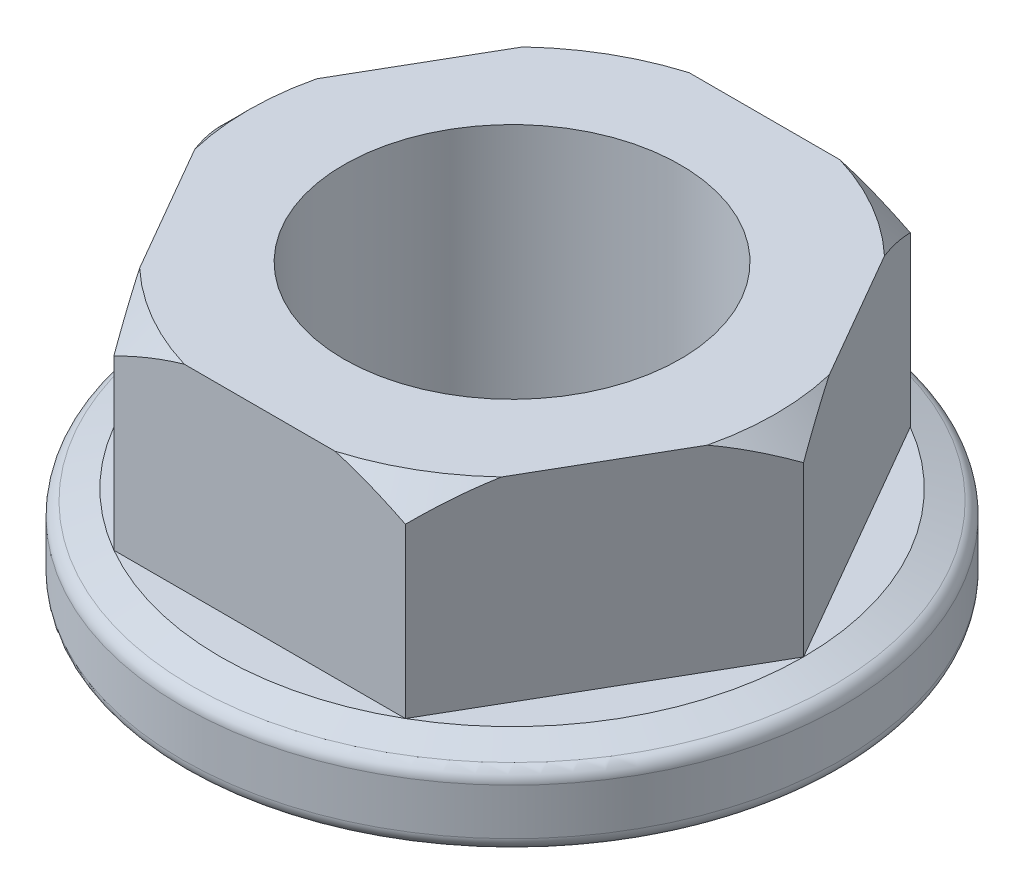
SolidWorks part; units mm, degrees
ref_plane "Front Plane" through (0, 0, 0) normal (0, 0, 1) x (1, 0, 0)
ref_plane "Top Plane" through (0, 0, 0) normal (0, 1, 0) x (1, 0, 0)
ref_plane "Right Plane" through (0, 0, 0) normal (1, 0, 0) x (0, 0, -1)
sketch "Sketch1" plane through (0, 0, 0) normal (0, 1, 0) x (1, 0, 0)
  line L1 (10.3923, 0) -> (5.1962, 9)
  line L2 (5.1962, 9) -> (-5.1962, 9)
  line L3 (-5.1962, 9) -> (-10.3923, 0)
  line L4 (-10.3923, 0) -> (-5.1962, -9)
  line L5 (-5.1962, -9) -> (5.1962, -9)
  line L6 (5.1962, -9) -> (10.3923, 0)
  circle A0 centre (0, 0) radius 9 construction
  circle A1 centre (0, 0) radius 6
  dimension "D2" = 12
  dimension "D1" = 18
extrude "Boss-Extrude1" add sketch "Sketch1" along normal blind 10
sketch "Sketch2" plane through (0, 0, 0) normal (0, -1, 0) x (1, 0, 0)
  line L1 (10.3923, 0) -> (5.1962, 9)
  line L2 (5.1962, 9) -> (-5.1962, 9)
  line L3 (-5.1962, 9) -> (-10.3923, 0)
  line L4 (-10.3923, 0) -> (-5.1962, -9)
  line L5 (-5.1962, -9) -> (5.1962, -9)
  line L6 (5.1962, -9) -> (10.3923, 0)
  circle A0 centre (0, 0) radius 11.75
  circle A1 centre (0, 0) radius 9 construction
  point P3 (10.3923, 0)
  dimension "D1" = 23.5
extrude "Boss-Extrude2" add sketch "Sketch2" against normal blind 3
sketch "Sketch3" plane through (0, 0, 0) normal (0, 0, 1) x (1, 0, 0)
  line L0 (-10.3923, 9) -> (-9.3923, 10)
  line L1 (-10.3923, 9) -> (-10.3923, 10)
  line L2 (-10.3923, 10) -> (-9.3923, 10)
  line L5 (-10.3923, 10) -> (-10.3923, 3) construction
  line L6 (-10.3923, 3) -> (-11.75, 2.5)
  line L7 (11.75, 3) -> (-11.75, 3) construction
  line L8 (-11.75, 3) -> (-11.75, 0) construction
  line L9 (-11.75, 2.5) -> (-11.75, 3)
  line L10 (-11.75, 3) -> (-10.3923, 3)
  line L11 (0, 0) -> (0, 50000) construction
  line L12 (-11.75, 0) -> (11.75, 0) construction
  point P2 (-10.3923, 3)
  point P10 (0, 0)
  dimension "D1" = 1
  dimension "D2" = 0.5
revolve "Cut-Revolve1" cut sketch "Sketch3" angle 360 about L11
fillet "Fillet1" radius 0.5 2 edges at (0, 0, -11.75) (0, 2.5, -11.75)
